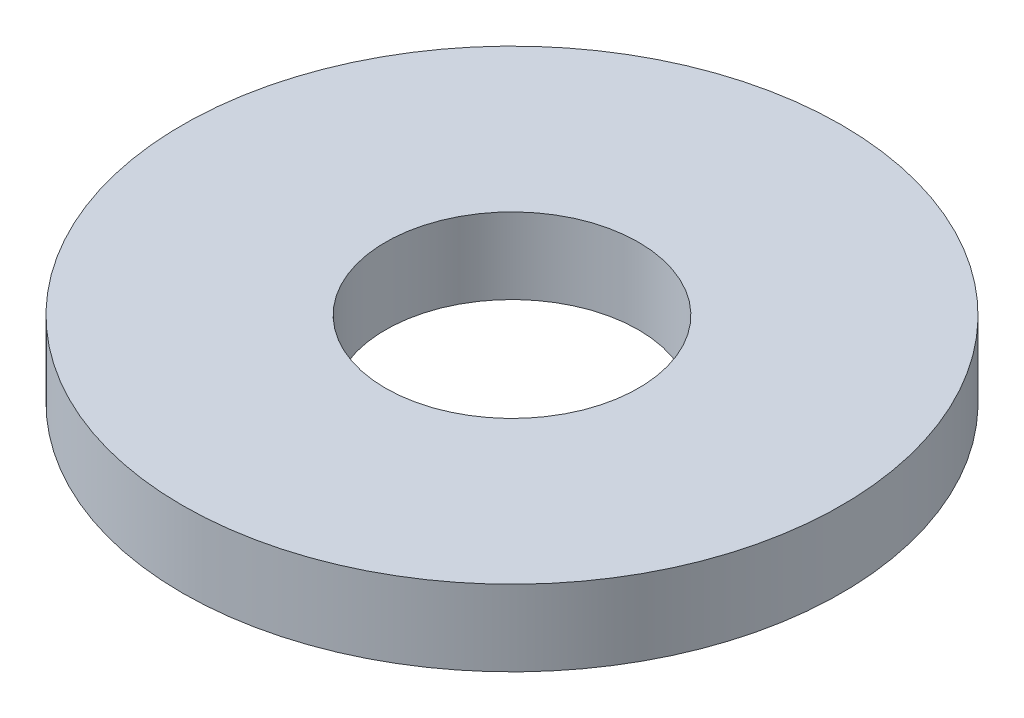
SolidWorks part; units mm, degrees
ref_plane "Front Plane" through (0, 0, 0) normal (0, 0, 1) x (1, 0, 0)
ref_plane "Top Plane" through (0, 0, 0) normal (0, 1, 0) x (1, 0, 0)
ref_plane "Right Plane" through (0, 0, 0) normal (1, 0, 0) x (0, 0, -1)
sketch "Sketch1" plane through (0, 0, 0) normal (0, 1, 0) x (1, 0, 0)
  circle A0 centre (0, 0) radius 2.413
  circle A1 centre (0, 0) radius 6.2865
  dimension "D1" = 4.826
  dimension "D2" = 12.573
extrude "Boss-Extrude1" add sketch "Sketch1" along normal blind 1.4478
